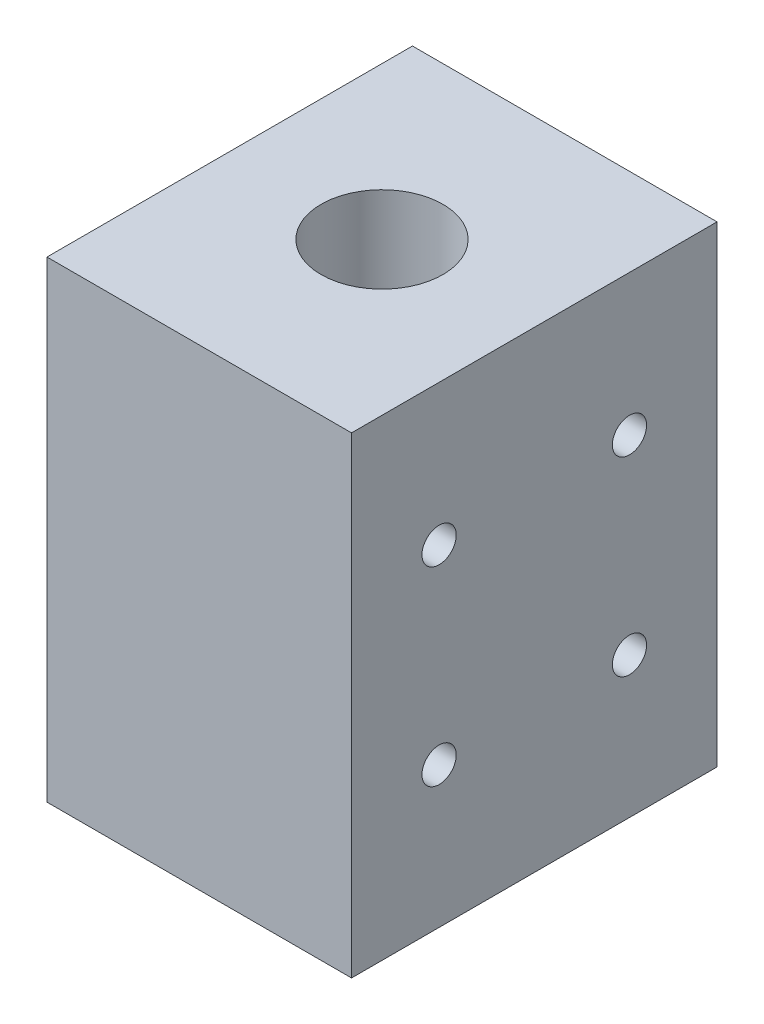
SolidWorks part; units mm, degrees
material "AISI 1035 Acero (SS)"
ref_plane "Alzado" through (0, 0, 0) normal (0, 0, 1) x (1, 0, 0)
ref_plane "Planta" through (0, 0, 0) normal (0, 1, 0) x (1, 0, 0)
ref_plane "Vista lateral" through (0, 0, 0) normal (1, 0, 0) x (0, 0, -1)
sketch "Croquis1" plane through (0, 0, 0) normal (0, 1, 0) x (1, 0, 0)
  line L1 (20, -24) -> (-20, -24)
  line L2 (20, -24) -> (20, 24)
  line L3 (20, 24) -> (-20, 24)
  line L4 (-20, -24) -> (-20, 24)
  line L5 (20, -24) -> (-20, 24) construction
  line L6 (20, 24) -> (-20, -24) construction
  circle A0 centre (0, 0) radius 8
  point P0 (0, 0)
  dimension "D1" = 48
  dimension "D2" = 40
extrude "Saliente-Extruir1" add sketch "Croquis1" along normal blind 62
sketch "Croquis2" plane through (20, 0, 0) normal (1, 0, 0) x (0, 0, -1)
  line L0 (-12.5, 18.5) -> (-12.5, 43.5) construction
  line L1 (-24, 62) -> (-24, 0) construction
  circle A0 centre (-12.5, 43.5) radius 2.25
  circle A1 centre (12.5, 43.5) radius 2.25
  circle A2 centre (-12.5, 18.5) radius 2.25
  circle A3 centre (12.5, 18.5) radius 2.25
  point P8 (-12.5, 31)
  point P11 (-24, 31)
  dimension "D1" = 25
  dimension "D2" = 12.5
  dimension "D3" = 25
extrude "Cortar-Extruir1" cut sketch "Croquis2" against normal blind 30
